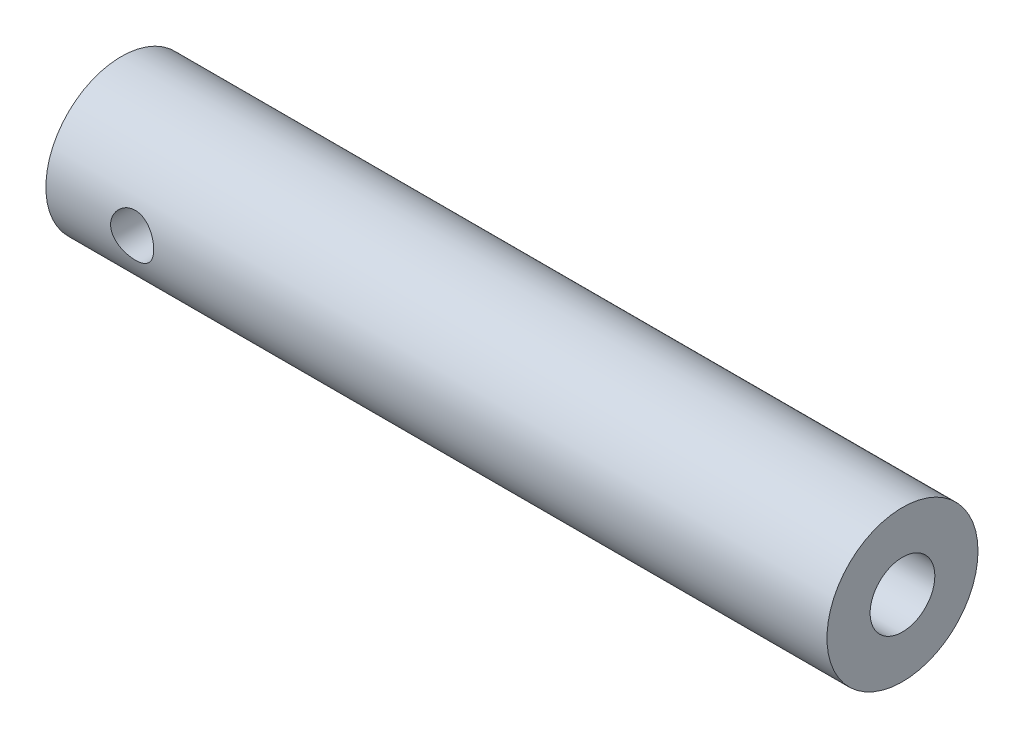
SolidWorks part; units mm, degrees
ref_plane "Front Plane" through (0, 0, 0) normal (0, 0, 1) x (1, 0, 0)
ref_plane "Top Plane" through (0, 0, 0) normal (0, 1, 0) x (1, 0, 0)
ref_plane "Right Plane" through (0, 0, 0) normal (1, 0, 0) x (0, 0, -1)
sketch "Sketch2" plane through (0, 0, 0) normal (1, 0, 0) x (0, 0, -1)
  circle A0 centre (0, 0) radius 17.5
extrude "Boss-Extrude1" add sketch "Sketch2" along normal blind 181 contours A0
ref_plane "Plane1" through (0, 0, 17.5) normal (0, 0, 1) x (1, 0, 0)
sketch "Sketch3" plane through (0, 0, 17.5) normal (0, 0, 1) x (1, 0, 0)
  circle A0 centre (20, 0) radius 5
extrude "Cut-Extrude1" cut sketch "Sketch3" against normal blind 181
sketch "Sketch4" plane through (181, 0, 0) normal (1, 0, 0) x (0, 0, -1)
  circle A0 centre (0, 0) radius 7.5
extrude "Cut-Extrude2" cut sketch "Sketch4" against normal blind 20 contours A0
sketch "Sketch5" plane through (161, 0, 0) normal (1, 0, 0) x (0, 0, -1)
  circle A0 centre (0, 0) radius 12.5
extrude "Cut-Extrude3" cut sketch "Sketch5" against normal blind 20
